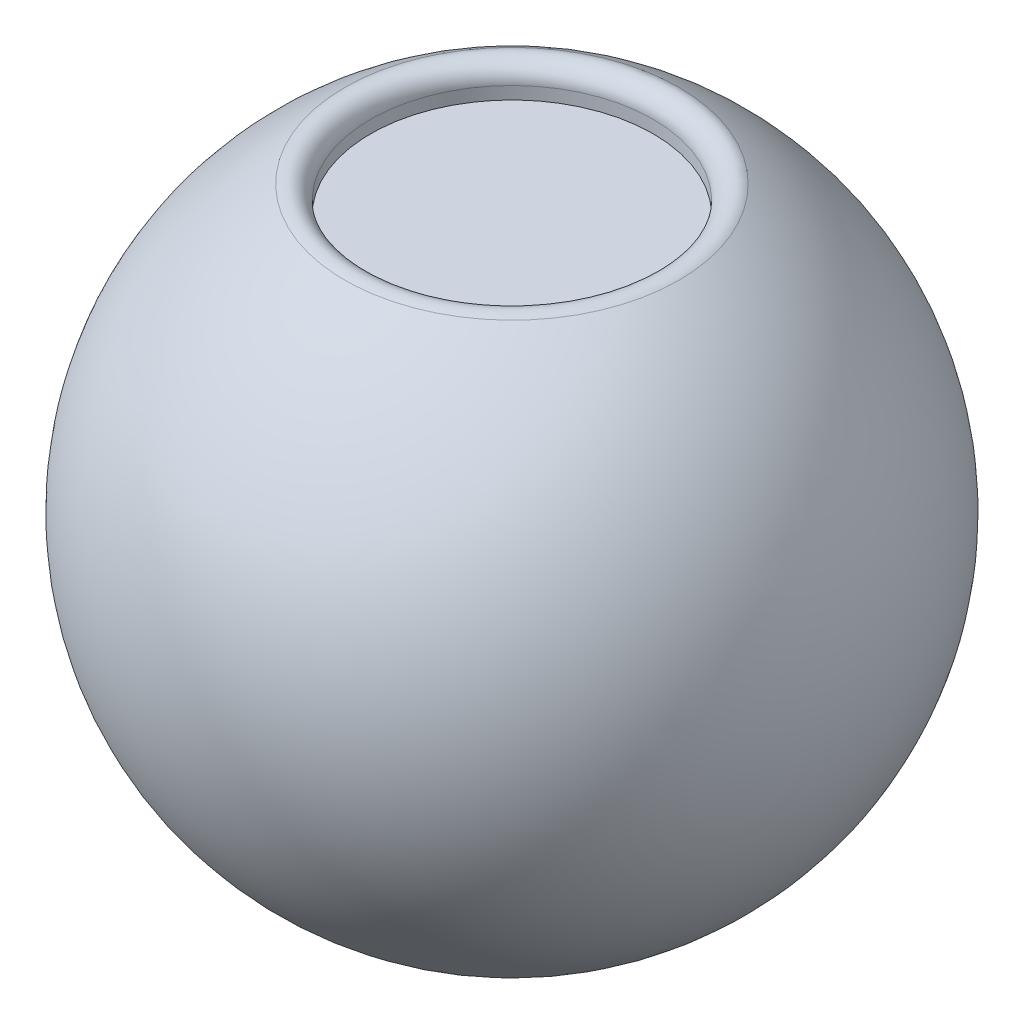
SolidWorks part; units mm, degrees
ref_plane "Ön Düzlem" through (0, 0, 0) normal (0, 0, 1) x (1, 0, 0)
ref_plane "Üst Düzlem" through (0, 0, 0) normal (0, 1, 0) x (1, 0, 0)
ref_plane "Sağ Düzlem" through (0, 0, 0) normal (1, 0, 0) x (0, 0, -1)
sketch "Çizim2" plane through (0, 0, 0) normal (0, 0, 1) x (1, 0, 0)
  line L0 (77, 0) -> (0, 0)
  arc A0 (0, 0) -> (77, 0) centre (38.5, 0) cw
  point P3 (34.6798, -16.7202)
  point P5 (0, 0)
  dimension "D1" = 38.5
revolve "Döndür1" add sketch "Çizim2" angle 360 about L0
sketch "Çizim3" plane through (0, 0, 0) normal (0, 1, 0) x (1, 0, 0)
  line L0 (6.7, 40.6087) -> (6.7, -42.4639)
  line L1 (6.7, -42.4639) -> (0, -42.4639)
  line L2 (0, -42.4639) -> (0, 40.6087)
  line L3 (0, 40.6087) -> (6.7, 40.6087)
  point P2 (23.6582, 39.9903)
  dimension "D1" = 6.7
extrude "Kes-Ekstrüzyon1" cut sketch "Çizim3" against normal through all and the other way through all
sketch "Çizim4" plane through (0, 0, 0) normal (0, 1, 0) x (1, 0, 0)
  circle A0 centre (38.5, 0) radius 16.5
  dimension "D1" = 33
extrude "Kes-Ekstrüzyon2" cut sketch "Çizim4" along normal through all from offset 30
fillet "Radyus1" radius 2 1 edges at (38.5, 34.7851, -16.5)
